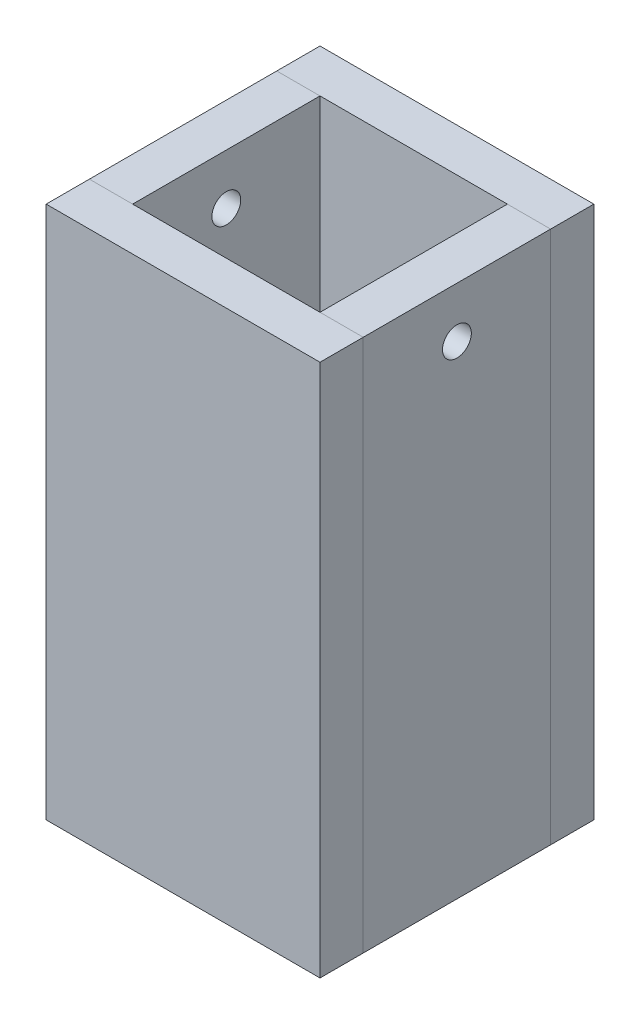
SolidWorks part; units mm, degrees
ref_plane "Plano frontal" through (0, 0, 0) normal (0, 0, 1) x (1, 0, 0)
ref_plane "Plano superior" through (0, 0, 0) normal (0, 1, 0) x (1, 0, 0)
ref_plane "Plano direito" through (0, 0, 0) normal (1, 0, 0) x (0, 0, -1)
sketch "Esboço1" plane through (0, 0, 0) normal (0, 1, 0) x (1, 0, 0)
  line L0 (19, -19) -> (19, -13)
  line L1 (19, -13) -> (-19, -13)
  line L2 (19, 19) -> (-19, 19)
  line L3 (19, -19) -> (-19, -19)
  line L4 (-19, -13) -> (-19, -19)
  line L5 (-19, 19) -> (-19, 13)
  line L6 (-19, 13) -> (19, 13)
  line L7 (19, 13) -> (19, 19)
extrude "Ressalto-extrusão1" add sketch "Esboço1" along normal blind 74
sketch "Esboço2" plane through (0, 0, -13) normal (0, 0, 1) x (1, 0, 0)
  line L0 (19, 74) -> (13, 74)
  line L1 (-19, 74) -> (19, 74) construction
  line L2 (13, 74) -> (13, 0)
  line L3 (-19, 0) -> (19, 0) construction
  line L4 (13, 0) -> (19, 0)
  line L5 (19, 0) -> (19, 74)
  line L6 (-19, 0) -> (-13, 0)
  line L7 (-13, 0) -> (-13, 74)
  line L8 (-13, 74) -> (-19, 74)
  line L9 (-19, 74) -> (-19, 0)
extrude "Ressalto-extrusão2" add sketch "Esboço2" along normal up to surface (26 mm away) separate body up to face at (0, 37, 13)
sketch "Esboço3" plane through (19, 0, 0) normal (1, 0, 0) x (0, 0, -1)
  circle A0 centre (0, 67) radius 2
extrude "Corte_tubo" cut sketch "Esboço3" against normal up to surface (38 mm away)
